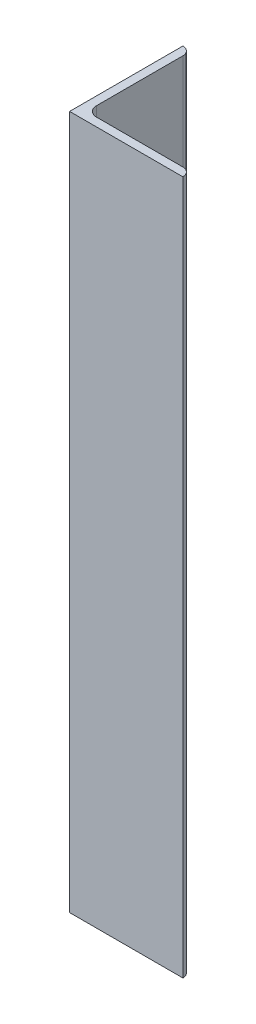
SolidWorks part; units mm, degrees
ref_plane "Front Plane" through (0, 0, 0) normal (0, 0, 1) x (1, 0, 0)
ref_plane "Top Plane" through (0, 0, 0) normal (0, 1, 0) x (1, 0, 0)
ref_plane "Right Plane" through (0, 0, 0) normal (1, 0, 0) x (0, 0, -1)
sketch3d "3DSketch1"
  line L0 (0, 0, 0) -> (0, 245, 0)
  dimension "D1" = 245
other "Iron V40X40X3(1)"
ref_plane "Plane1" through (0, 0, 0) normal (0, 1, 0) x (1, 0, 0)
sketch "Sketch1" plane through (0, 0, 0) normal (0, 1, 0) x (1, 0, 0)
  line L0 (0, 0) -> (0, 40)
  line L1 (0, 20) -> (3, 20) construction
  line L2 (3, 37) -> (3, 6.5)
  line L3 (6.5, 3) -> (37, 3)
  line L4 (20, 3) -> (20, 0) construction
  line L5 (40, 0) -> (0, 0)
  arc A0 (40, 0) -> (37, 3) centre (37, 0) ccw
  arc A1 (0, 40) -> (3, 37) centre (0, 37) cw
  arc A2 (6.5, 3) -> (3, 6.5) centre (6.5, 6.5) cw
  point P10 (20, 0)
  point P14 (0, 20)
  point P15 (3, 20)
  point P16 (20, 3)
  point P17 (3, 40)
  point P18 (40, 3)
  point P21 (0, 0)
  dimension "D2" = 3
  dimension "D3" = 40
  dimension "Radius_1" = 3.5
  dimension "D1" = 3
sketch "Sketch2" plane through (0, 0, 0) normal (-1, 0, 0) x (0, 0, 1)
  line L0 (-25.5, 165) -> (-10.5, 165) construction
  line L1 (-25.5, 170) -> (-10.5, 170)
  line L2 (-25.5, 160) -> (-10.5, 160)
  line L3 (-40, 0) -> (0, 0) construction
  line L5 (-25.5, 195) -> (-10.5, 195) construction
  line L6 (-25.5, 200) -> (-10.5, 200)
  line L7 (-25.5, 190) -> (-10.5, 190)
  line L8 (0, 0) -> (0, 245) construction
  arc A0 (-25.5, 170) -> (-25.5, 160) centre (-25.5, 165) ccw
  arc A1 (-10.5, 160) -> (-10.5, 170) centre (-10.5, 165) ccw
  arc A2 (-25.5, 200) -> (-25.5, 190) centre (-25.5, 195) ccw
  arc A3 (-10.5, 190) -> (-10.5, 200) centre (-10.5, 195) ccw
  point P2 (-18, 165)
  point P14 (-18, 195)
  dimension "D2" = 5
  dimension "D4" = 18
  dimension "D1" = 15
  dimension "D3" = 165
  dimension "D5" = 2
extrude "Cut-Extrude1" cut sketch "Sketch2" against normal blind 10
